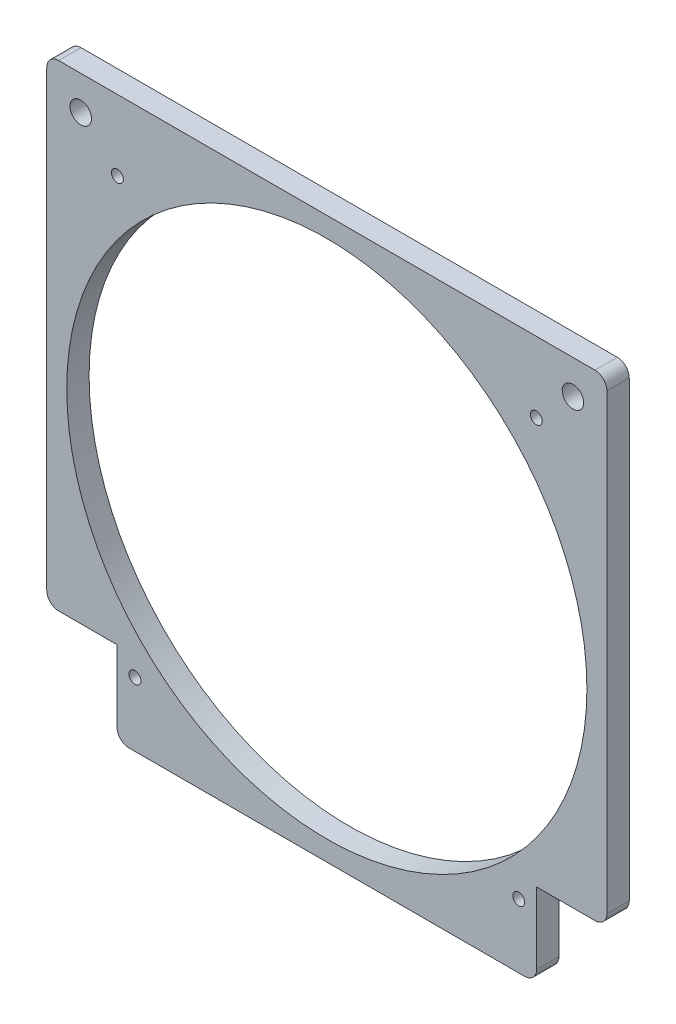
SolidWorks part; units mm, degrees
ref_plane "Front Plane" through (0, 0, 0) normal (0, 0, 1) x (1, 0, 0)
ref_plane "Top Plane" through (0, 0, 0) normal (0, 1, 0) x (1, 0, 0)
ref_plane "Right Plane" through (0, 0, 0) normal (1, 0, 0) x (0, 0, -1)
sketch "Sketch1" plane through (0, 0, 0) normal (0, 0, 1) x (1, 0, 0)
  line L1 (-90.8866, 92.7392) -> (28.4934, 92.7392)
  line L2 (-90.8866, 92.7392) -> (-90.8866, -26.6408)
  line L3 (-90.8866, -26.6408) -> (28.4934, -26.6408)
  line L4 (28.4934, 92.7392) -> (28.4934, -26.6408)
  line L5 (-90.8866, 92.7392) -> (28.4934, -26.6408) construction
  line L6 (-90.8866, -26.6408) -> (28.4934, 92.7392) construction
  point P0 (-31.1966, 33.0492)
  dimension "D1" = 119.38
  dimension "D2" = 119.38
extrude "Boss-Extrude1" add sketch "Sketch1" along normal blind 4.7625
sketch "Sketch2" plane through (0, 0, 0) normal (0, 0, -1) x (-1, 0, 0)
  line L0 (73.3606, -16.1633) -> (-10.9674, -16.1633) construction
  line L1 (31.1966, 92.7392) -> (31.1966, -26.6408) construction
  line L2 (-28.4934, 92.7392) -> (90.8866, 92.7392) construction
  line L3 (90.8866, -26.6408) -> (-28.4934, -26.6408) construction
  line L4 (-28.4934, 33.0492) -> (91.3946, 32.7952) construction
  line L5 (-28.4934, -26.6408) -> (-28.4934, 92.7392) construction
  line L6 (91.3946, -30.3238) -> (91.3946, 95.9142) construction
  circle A0 centre (-21.2544, 85.5002) radius 2.286
  circle A1 centre (83.6476, 85.5002) radius 2.286
  circle A4 centre (72.0906, -12.9883) radius 1.27
  circle A6 centre (31.1966, 33.0492) radius 55.4291
  circle A7 centre (-13.4439, 77.6897) radius 1.27
  circle A8 centre (75.8371, 77.6897) radius 1.27
  circle A9 centre (-9.6974, -12.9883) radius 1.27
  dimension "D1" = 4.572
  dimension "D2" = 4.572
  dimension "D5" = 2.54
  dimension "D6" = 2.54
  dimension "D9" = 3.175
extrude "Cut-Extrude1" cut sketch "Sketch2" against normal up to next
sketch "Sketch4" plane through (0, 0, 0) normal (0, 0, -1) x (-1, 0, 0)
  line L0 (-28.4934, -26.6408) -> (-28.4934, 92.7392) construction
  line L1 (-28.4934, -26.6408) -> (-13.5074, -26.6408)
  line L2 (-28.4934, -26.6408) -> (-28.4934, -8.8608)
  line L3 (-28.4934, -8.8608) -> (-13.5074, -8.8608)
  line L4 (-13.5074, -26.6408) -> (-13.5074, -8.8608)
  line L5 (90.8866, -26.6408) -> (-28.4934, -26.6408) construction
  line L6 (31.1966, 92.7392) -> (31.1966, -26.6408) construction
  line L7 (-28.4934, 92.7392) -> (90.8866, 92.7392) construction
  line L8 (75.9006, -26.6408) -> (75.9006, -8.8608)
  line L9 (90.8866, -8.8608) -> (75.9006, -8.8608)
  line L10 (90.8866, -26.6408) -> (90.8866, -8.8608)
  line L11 (90.8866, -26.6408) -> (75.9006, -26.6408)
  dimension "D1" = 17.78
  dimension "D2" = 14.986
extrude "Cut-Extrude2" cut sketch "Sketch4" against normal up to next
fillet "Fillet2" radius 2.54 2 edges at (-90.8866, 92.7392, 2.3813) (28.4934, 92.7392, 2.3813)
fillet "Fillet3" radius 2.54 4 edges at (13.5074, -26.6408, 2.3813) (28.4934, -8.8608, 2.3813) (-75.9006, -26.6408, 2.3813) (-90.8866, -8.8608, 2.3813)
